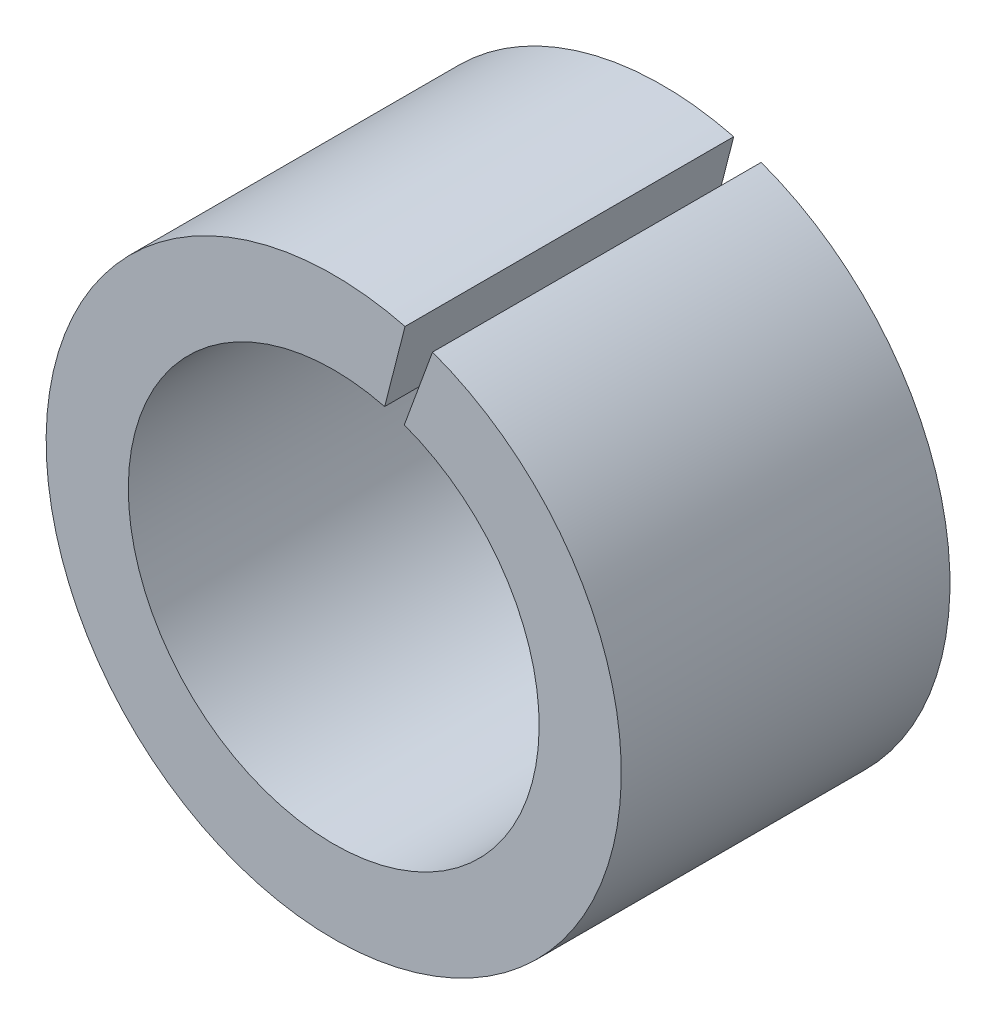
SolidWorks part; units mm, degrees
ref_plane "前视基准面" through (0, 0, 0) normal (0, 0, 1) x (1, 0, 0)
ref_plane "上视基准面" through (0, 0, 0) normal (0, 1, 0) x (1, 0, 0)
ref_plane "右视基准面" through (0, 0, 0) normal (1, 0, 0) x (0, 0, -1)
sketch "草图1" plane through (0, 0, 0) normal (0, 0, 1) x (1, 0, 0)
  circle A0 centre (0, 0) radius 3.5
  circle A1 centre (0, 0) radius 2.5
  dimension "D1" = 5
  dimension "D2" = 7
extrude "凸台-拉伸1" add sketch "草图1" along normal blind 4
sketch "草图2" plane through (0, 0, 4) normal (0, 0, 1) x (1, 0, 0)
  line L0 (0, 0) -> (1.1956, 4.6702)
  line L1 (1.1956, 4.6702) -> (1.7082, 4.6702)
  line L2 (1.7082, 4.6702) -> (0, 0)
extrude "切除-拉伸1" cut sketch "草图2" against normal blind 6
